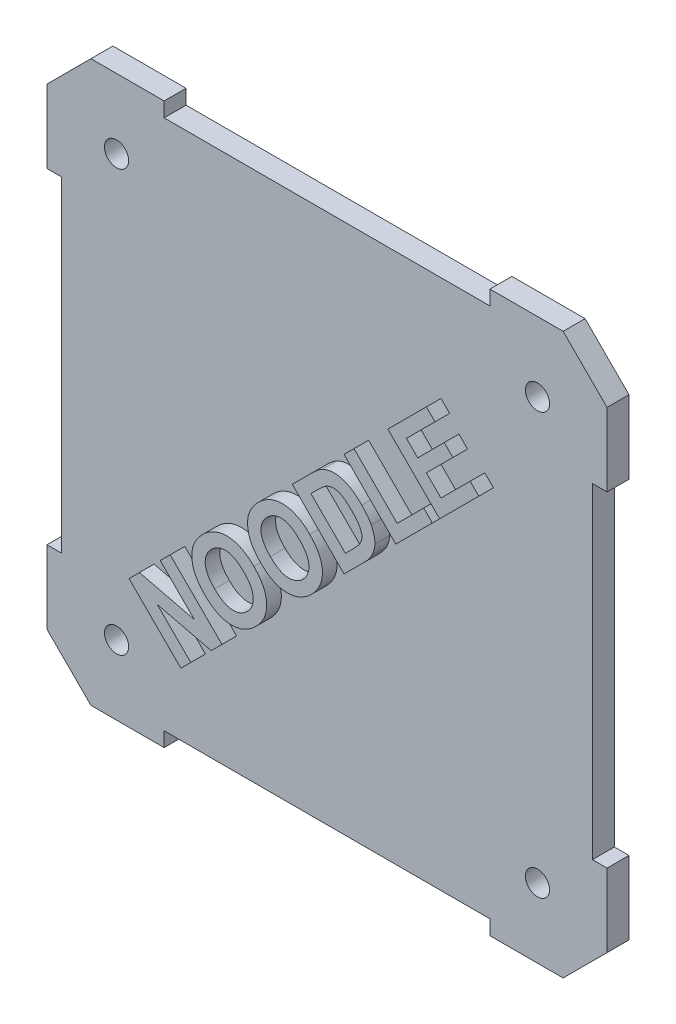
SolidWorks part; units mm, degrees
ref_plane "Front Plane" through (0, 0, 0) normal (0, 0, 1) x (1, 0, 0)
ref_plane "Top Plane" through (0, 0, 0) normal (0, 1, 0) x (1, 0, 0)
ref_plane "Right Plane" through (0, 0, 0) normal (1, 0, 0) x (0, 0, -1)
sketch "Sketch1" plane through (0, 0, 0) normal (0, 0, 1) x (1, 0, 0)
  line L0 (0, -55) -> (0, 55) construction
  line L1 (38.25, -38.25) -> (22.25, -38.25)
  line L2 (38.25, -38.25) -> (38.25, -22.25)
  line L3 (38.25, 38.25) -> (22.25, 38.25)
  line L4 (-38.25, -38.25) -> (-38.25, -22.25)
  line L5 (38.25, -38.25) -> (-38.25, 38.25) construction
  line L6 (38.25, 38.25) -> (-38.25, -38.25) construction
  line L8 (-22.25, 38.25) -> (-22.25, 36.25)
  line L9 (-22.25, 36.25) -> (22.25, 36.25)
  line L10 (22.25, 38.25) -> (22.25, 36.25)
  line L11 (-22.25, 38.25) -> (-38.25, 38.25)
  line L12 (36.25, 22.25) -> (36.25, -22.25)
  line L13 (38.25, 22.25) -> (36.25, 22.25)
  line L14 (38.25, -22.25) -> (36.25, -22.25)
  line L15 (22.25, -36.25) -> (-22.25, -36.25)
  line L16 (22.25, -38.25) -> (22.25, -36.25)
  line L17 (-22.25, -38.25) -> (-22.25, -36.25)
  line L18 (-36.25, -22.25) -> (-36.25, 22.25)
  line L19 (-38.25, -22.25) -> (-36.25, -22.25)
  line L20 (-38.25, 22.25) -> (-36.25, 22.25)
  line L21 (-38.25, 22.25) -> (-38.25, 38.25)
  line L22 (-22.25, -38.25) -> (-38.25, -38.25)
  line L23 (38.25, 22.25) -> (38.25, 38.25)
  circle A0 centre (-28.75, 28.75) radius 1.65
  circle A1 centre (28.75, 28.75) radius 1.65
  circle A2 centre (28.75, -28.75) radius 1.65
  circle A3 centre (-28.75, -28.75) radius 1.65
  point P0 (0, 0)
  point P10 (0, 36.25)
  point P28 (0, 0)
  point P37 (0, 0)
  dimension "D5" = 3.3
  dimension "D1" = 76.5
  dimension "D2" = 2
  dimension "D3" = 44.5
  dimension "D6" = 9.5
  dimension "D4" = 4
  dimension "D7" = 4
extrude "Boss-Extrude1" add sketch "Sketch1" along normal blind 3
chamfer "Chamfer1" distance 6 angle 45 4 edges at (-38.25, -38.25, 1.5) (38.25, -38.25, 1.5) (-38.25, 38.25, 1.5) (38.25, 38.25, 1.5)
sketch "Sketch2" plane through (-5.7483, 4.3654, 3) normal (0, 0, 1) x (0.7071, 0.7071, 0)
  line L2 (0.9779, -7.1514) -> (0.9779, 14.4417) construction
  line L3 (-39.6808, -7.1514) -> (41.6365, -7.1514) construction
  text T0 "<b>NOODLE</b>" font "Arial" height 10
extrude "Boss-Extrude2" add sketch "Sketch2" along normal blind 2
